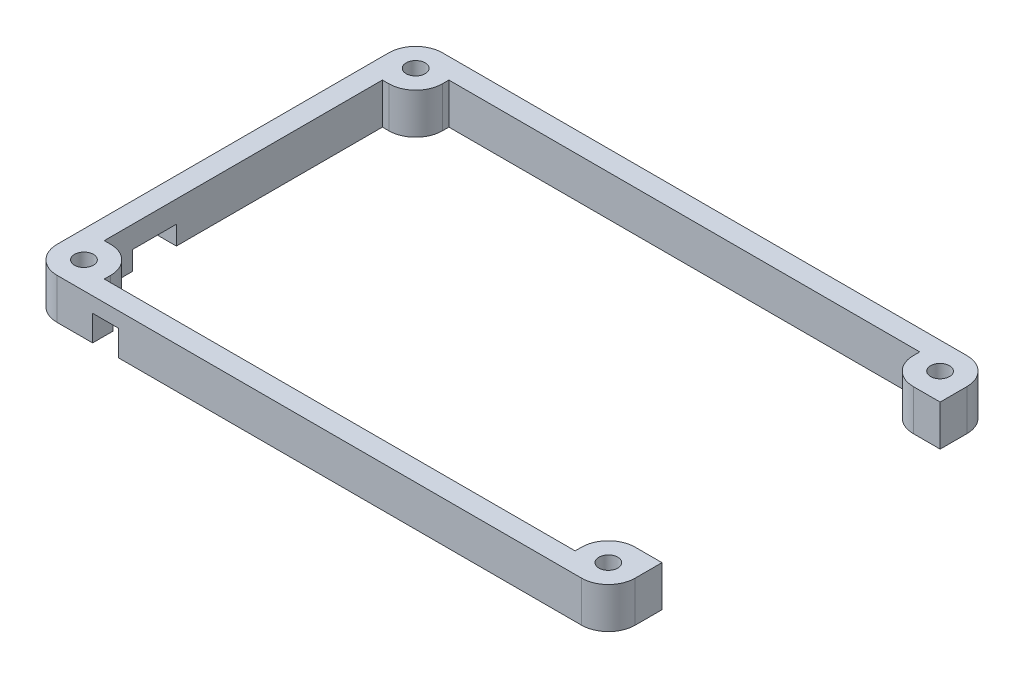
SolidWorks part; units mm, degrees
material "Rubber"
ref_plane "Front" through (0, 0, 0) normal (0, 0, 1) x (1, 0, 0)
ref_plane "Top" through (0, 0, 0) normal (0, 1, 0) x (1, 0, 0)
ref_plane "Right" through (0, 0, 0) normal (1, 0, 0) x (0, 0, -1)
sketch "Sketch1" plane through (0, 0, 0) normal (0, 1, 0) x (1, 0, 0)
  line L0 (-45, 0) -> (45, 0) construction
  line L1 (-45, 30) -> (45, 30) construction
  line L2 (-45, 30) -> (-45, -30) construction
  line L3 (-45, -30) -> (45, -30) construction
  line L4 (45, 30) -> (45, -30) construction
  line L5 (0, -30) -> (0, 30) construction
  line L6 (41.825, 26.825) -> (41.825, -26.825) construction
  line L7 (-41.825, -26.825) -> (41.825, -26.825) construction
  line L8 (-41.825, 26.825) -> (-41.825, -26.825) construction
  line L9 (-41.825, 26.825) -> (41.825, 26.825) construction
  line L10 (40.825, 25.825) -> (40.825, -25.825) construction
  line L11 (-40.825, -25.825) -> (40.825, -25.825) construction
  line L12 (-40.825, 25.825) -> (-40.825, -25.825) construction
  line L13 (-40.825, 25.825) -> (40.825, 25.825) construction
  line L14 (40.825, 21.65) -> (45, 21.65) construction
  line L15 (40.825, -21.65) -> (45, -21.65) construction
  line L16 (36.65, -25.825) -> (36.65, -30) construction
  line L17 (-36.65, -25.825) -> (-36.65, -30) construction
  line L18 (-40.825, -21.65) -> (-45, -21.65) construction
  line L19 (-36.65, 25.825) -> (-36.65, 30) construction
  line L20 (-40.825, 21.65) -> (-45, 21.65) construction
  line L21 (36.65, 25.825) -> (36.65, 30) construction
  line L22 (40.825, -25.825) -> (41.825, -25.825) construction
  circle A0 centre (-40.825, -25.825) radius 1 construction
  circle A1 centre (40.825, -25.825) radius 1 construction
  circle A2 centre (40.825, 25.825) radius 1 construction
  circle A3 centre (-40.825, 25.825) radius 1 construction
  circle A4 centre (40.825, -25.825) radius 4.175 construction
  circle A5 centre (40.825, 25.825) radius 4.175 construction
  circle A6 centre (-40.825, 25.825) radius 4.175 construction
  circle A7 centre (-40.825, -25.825) radius 4.175 construction
  dimension "D1" = 90
  dimension "D2" = 60
  dimension "D4" = 1
  dimension "D3" = 3.175
sketch "Sketch2" plane through (0, 0, 0) normal (0, 1, 0) x (1, 0, 0)
  line L0 (-45, 30) -> (-45, -30) construction
  line L1 (-45, -30) -> (45, -30) construction
  line L2 (45, 30) -> (45, -30) construction
  line L3 (-45, 30) -> (45, 30) construction
  line L4 (40.825, 21.65) -> (45, 21.65) construction
  line L5 (36.65, 25.825) -> (36.65, 30) construction
  line L6 (-36.65, 25.825) -> (-36.65, 30) construction
  line L7 (-40.825, 21.65) -> (-45, 21.65) construction
  line L8 (-36.65, -25.825) -> (-36.65, -30) construction
  line L9 (-40.825, -21.65) -> (-45, -21.65) construction
  line L10 (36.65, -25.825) -> (36.65, -30) construction
  line L11 (40.825, -21.65) -> (45, -21.65) construction
  line L16 (-45, 25.825) -> (-45, -25.825)
  line L17 (-40.825, -30) -> (40.825, -30)
  line L18 (45, 25.825) -> (45, -25.825)
  line L19 (-40.825, 30) -> (40.825, 30)
  line L20 (40.825, 21.65) -> (41.825, 21.65)
  line L21 (36.65, 25.825) -> (36.65, 26.825)
  line L22 (-36.65, 25.825) -> (-36.65, 26.825)
  line L23 (-40.825, 21.65) -> (-41.825, 21.65)
  line L24 (-36.65, -25.825) -> (-36.65, -26.825)
  line L25 (-40.825, -21.65) -> (-41.825, -21.65)
  line L26 (36.65, -25.825) -> (36.65, -26.825)
  line L27 (40.825, -21.65) -> (41.825, -21.65)
  line L28 (41.825, 26.825) -> (41.825, -26.825) construction
  line L29 (-36.65, -26.825) -> (36.65, -26.825)
  line L30 (-41.825, 26.825) -> (41.825, 26.825) construction
  line L31 (-41.825, 26.825) -> (-41.825, -26.825) construction
  line L32 (-36.65, 26.825) -> (36.65, 26.825)
  line L33 (-41.825, 21.65) -> (-41.825, -21.65)
  line L34 (41.825, 21.65) -> (41.825, -21.65)
  line L35 (-41.825, -26.825) -> (41.825, -26.825) construction
  circle A0 centre (40.825, 25.825) radius 4.175 construction
  circle A1 centre (40.825, 25.825) radius 1 construction
  circle A2 centre (-40.825, 25.825) radius 4.175 construction
  circle A3 centre (-40.825, 25.825) radius 1 construction
  circle A4 centre (-40.825, -25.825) radius 4.175 construction
  circle A5 centre (40.825, -25.825) radius 4.175 construction
  arc A6 (45, 25.825) -> (40.825, 30) centre (40.825, 25.825) ccw
  circle A7 centre (40.825, 25.825) radius 1 construction
  arc A8 (-40.825, 30) -> (-45, 25.825) centre (-40.825, 25.825) ccw
  circle A9 centre (-40.825, 25.825) radius 1 construction
  arc A10 (-36.65, -25.825) -> (-40.825, -21.65) centre (-40.825, -25.825) ccw
  arc A11 (40.825, -21.65) -> (36.65, -25.825) centre (40.825, -25.825) ccw
  circle A12 centre (-40.825, -25.825) radius 1 construction
  circle A13 centre (40.825, -25.825) radius 1 construction
  circle A14 centre (-40.825, -25.825) radius 1 construction
  circle A15 centre (40.825, -25.825) radius 1 construction
  arc A16 (-40.825, 21.65) -> (-36.65, 25.825) centre (-40.825, 25.825) ccw
  arc A17 (-45, -25.825) -> (-40.825, -30) centre (-40.825, -25.825) ccw
  arc A18 (40.825, -30) -> (45, -25.825) centre (40.825, -25.825) ccw
  arc A19 (36.65, 25.825) -> (40.825, 21.65) centre (40.825, 25.825) ccw
extrude "Boss-Extrude3" add sketch "Sketch2" along normal blind 6.35
sketch "Sketch5" plane through (-45, 0, 0) normal (-1, 0, 0) x (0, 0, 1)
  line L0 (13.825, 0) -> (25.825, 0) construction
  line L1 (25.825, 6.35) -> (25.825, 0) construction
  line L3 (17.225, 2.95) -> (10.425, 2.95)
  line L4 (17.225, 2.95) -> (17.225, -2.95)
  line L5 (17.225, -2.95) -> (10.425, -2.95)
  line L6 (10.425, 2.95) -> (10.425, -2.95)
  line L7 (17.225, 2.95) -> (10.425, -2.95) construction
  line L8 (17.225, -2.95) -> (10.425, 2.95) construction
  dimension "D1" = 12
  dimension "D2" = 6.8
  dimension "D3" = 5.9
extrude "Cut-Extrude3" cut sketch "Sketch5" against normal up to surface (3.175 mm away) up to face at (-41.825, 3.175, 0)
sketch "Sketch6" plane through (0, 0, 0) normal (0, -1, 0) x (1, 0, 0)
  circle A0 centre (40.825, 25.825) radius 1.4732
  circle A1 centre (40.825, -25.8149) radius 1.4732
  dimension "D1" = 2.9464
  dimension "D2" = 2.9464
sketch "Sketch7" plane through (0, 0, 0) normal (0, -1, 0) x (1, 0, 0)
  circle A0 centre (-40.825, -25.825) radius 1.475
  circle A1 centre (-40.825, 25.8136) radius 1.4732
  circle A2 centre (40.825, 25.825) radius 1.4732 construction
  circle A3 centre (40.825, 25.825) radius 1.4732
  circle A5 centre (40.825, -25.8149) radius 1.4732 construction
  circle A6 centre (40.825, -25.8149) radius 1.4732
  dimension "D1" = 2.95
  dimension "D2" = 2.9464
extrude "Cut-Extrude5" cut sketch "Sketch7" against normal up to surface (6.35 mm away) up to face at (0, 6.35, 0)
sketch "Sketch8" plane through (0, 6.35, 0) normal (0, 1, 0) x (1, 0, 0)
  line L0 (41.825, 21.65) -> (40.825, 21.65) construction
  line L1 (45, 21.65) -> (41.825, 21.65)
  line L2 (45, 21.65) -> (45, -21.65)
  line L3 (45, -21.65) -> (41.825, -21.65)
  line L4 (41.825, 21.65) -> (41.825, -21.65)
  line L5 (45, 21.65) -> (41.825, -21.65) construction
  line L6 (45, -21.65) -> (41.825, 21.65) construction
  line L7 (45, -25.825) -> (45, 25.825) construction
  point P0 (43.4125, 0)
extrude "Cut-Extrude6" cut sketch "Sketch8" against normal blind 10
sketch "Sketch9" plane through (0, 0, 30) normal (0, 0, 1) x (1, 0, 0)
  line L0 (-40.825, 0) -> (40.825, 0) construction
  line L1 (-31.2866, 4) -> (-35.2866, 4)
  line L2 (-31.2866, 4) -> (-31.2866, 0)
  line L3 (-31.2866, 0) -> (-35.2866, 0)
  line L4 (-35.2866, 4) -> (-35.2866, 0)
  line L5 (-31.2866, 4) -> (-35.2866, 0) construction
  line L6 (-31.2866, 0) -> (-35.2866, 4) construction
  dimension "D1" = 4
  dimension "D2" = 5.5384
  dimension "D3" = 4
extrude "Cut-Extrude8" cut sketch "Sketch9" against normal blind 4
